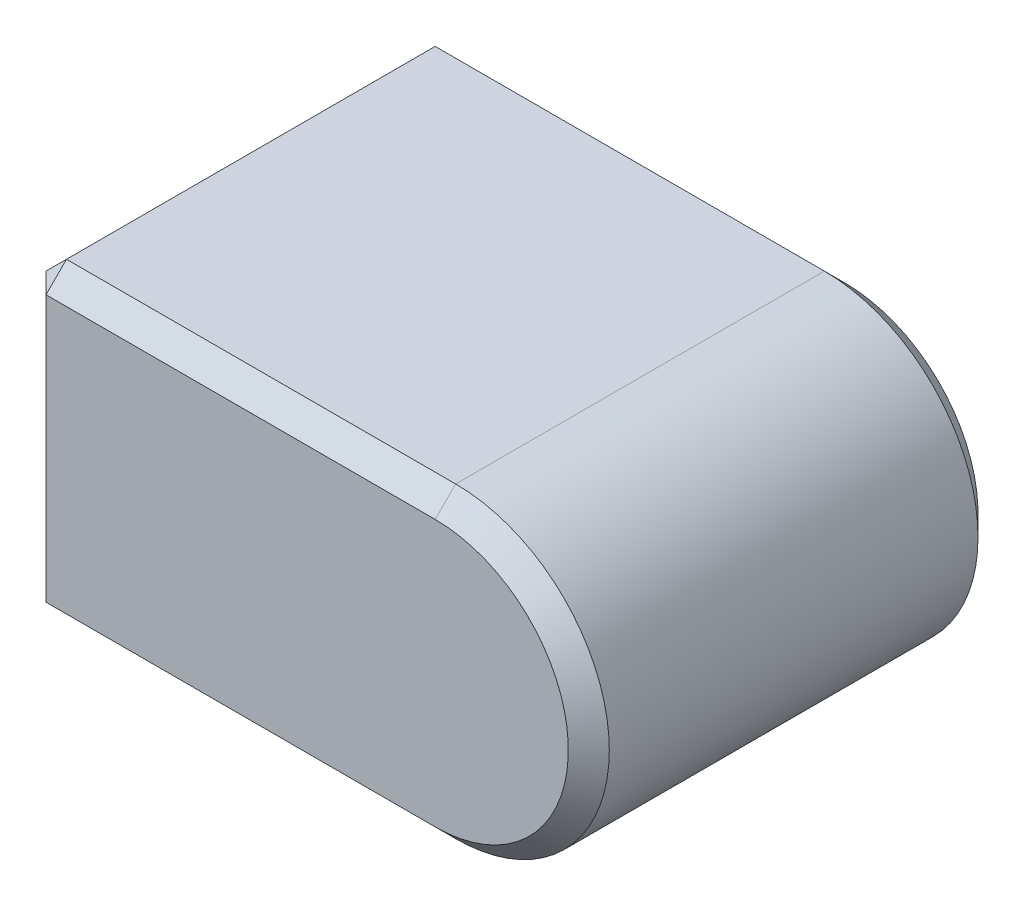
SolidWorks part; units mm, degrees
ref_plane "前视基准面" through (0, 0, 0) normal (0, 0, 1) x (1, 0, 0)
ref_plane "上视基准面" through (0, 0, 0) normal (0, 1, 0) x (1, 0, 0)
ref_plane "右视基准面" through (0, 0, 0) normal (1, 0, 0) x (0, 0, -1)
sketch "草图1" plane through (0, 0, 0) normal (0, 0, 1) x (1, 0, 0)
  line L3 (-2, -1.5) -> (2, -1.5)
  line L4 (-2, -1.5) -> (-2, 1.5)
  line L5 (-2, 1.5) -> (2, 1.5)
  line L6 (2, -1.5) -> (2, 1.5) construction
  line L7 (-2, -1.5) -> (2, 1.5) construction
  line L8 (-2, 1.5) -> (2, -1.5) construction
  arc A2 (2, -1.5) -> (2, 1.5) centre (2, 0) ccw
  arc A3 (0.56, 0.42) -> (0.56, -0.42) centre (2, 0) ccw construction
  arc A4 (2, 1.5) -> (0.56, 0.42) centre (2, 0) ccw construction
  arc A5 (0.56, -0.42) -> (2, -1.5) centre (2, 0) ccw construction
  point P0 (0, 0)
  dimension "D1" = 4
  dimension "D2" = 3
extrude "凸台-拉伸1" add sketch "草图1" along normal blind 4
chamfer "倒角1" distance 0.2 angle 45 10 edges at (-2, 1.5, 2) (-2, 0, 4) (-2, 0, 0) (0, 1.5, 0) (3.5, 0, 0) (0, -1.5, 0) (-2, -1.5, 2) (0, -1.5, 4) (3.5, 0, 4) (0, 1.5, 4)
